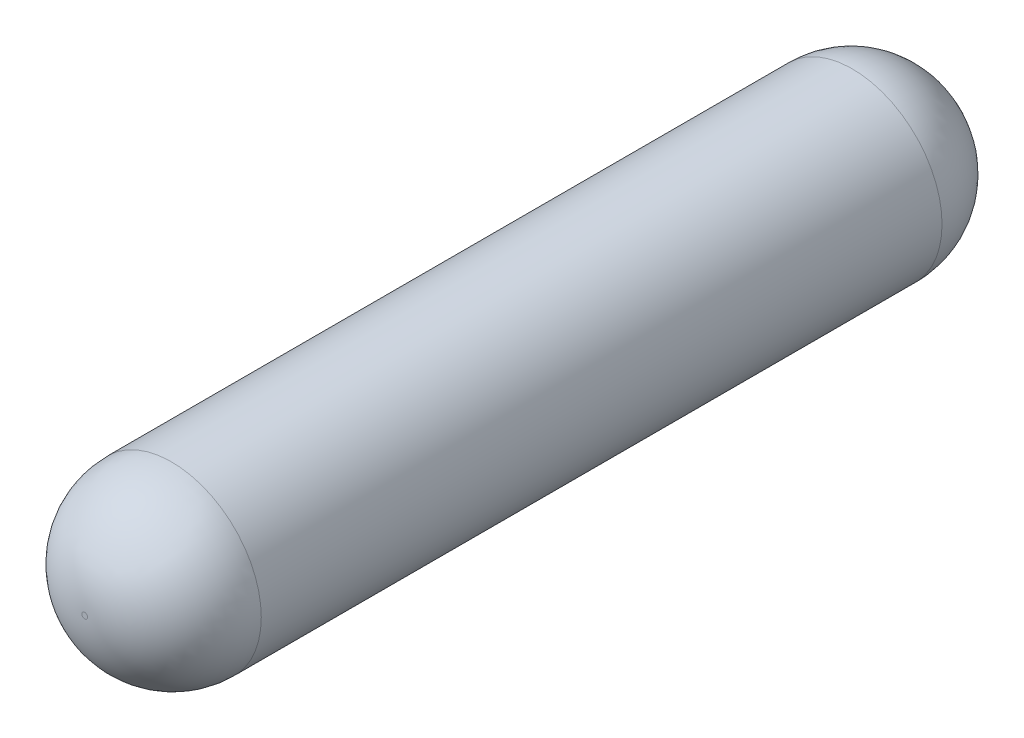
SolidWorks part; units mm, degrees
ref_plane "Front Plane" through (0, 0, 0) normal (0, 0, 1) x (1, 0, 0)
ref_plane "Top Plane" through (0, 0, 0) normal (0, 1, 0) x (1, 0, 0)
ref_plane "Right Plane" through (0, 0, 0) normal (1, 0, 0) x (0, 0, -1)
sketch "Sketch1" plane through (0, 0, 0) normal (0, 0, 1) x (1, 0, 0)
  circle A0 centre (0, 0) radius 6.3
  dimension "D1" = 12.6
extrude "Boss-Extrude1" add sketch "Sketch1" along normal blind 60
fillet "Fillet1" radius 6.1 2 edges at (6.3, 0, 0) (6.3, 0, 60)
